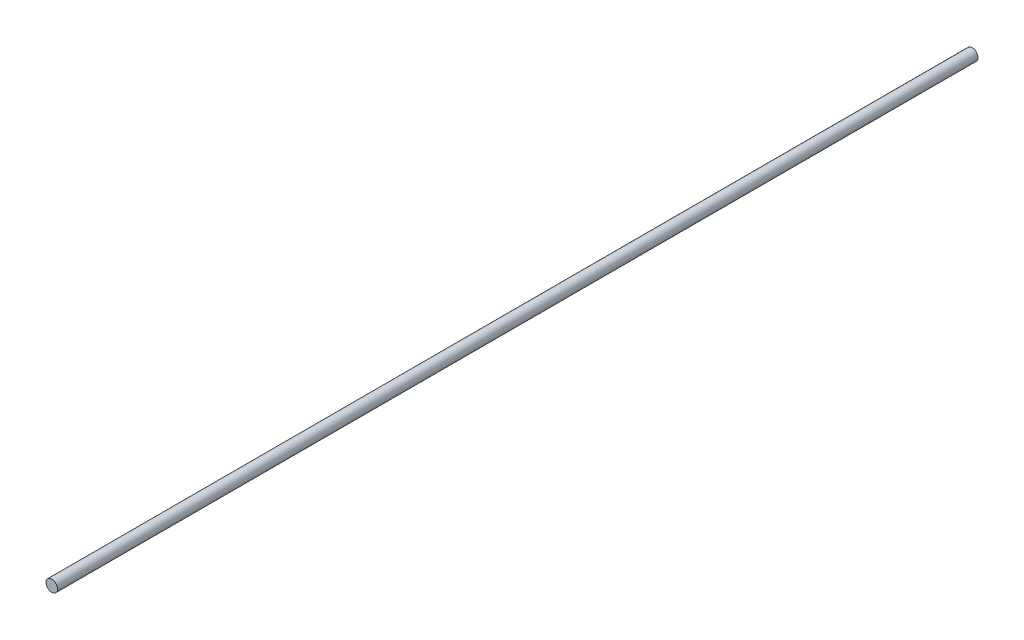
SolidWorks part; units mm, degrees
ref_plane "정면" through (0, 0, 0) normal (0, 0, 1) x (1, 0, 0)
ref_plane "윗면" through (0, 0, 0) normal (0, 1, 0) x (1, 0, 0)
ref_plane "우측면" through (0, 0, 0) normal (1, 0, 0) x (0, 0, -1)
sketch "스케치1" plane through (0, 0, 0) normal (0, 0, 1) x (1, 0, 0)
  circle A0 centre (0, 0) radius 4
extrude "보스-돌출1" add sketch "스케치1" along normal blind 640 contours A0
